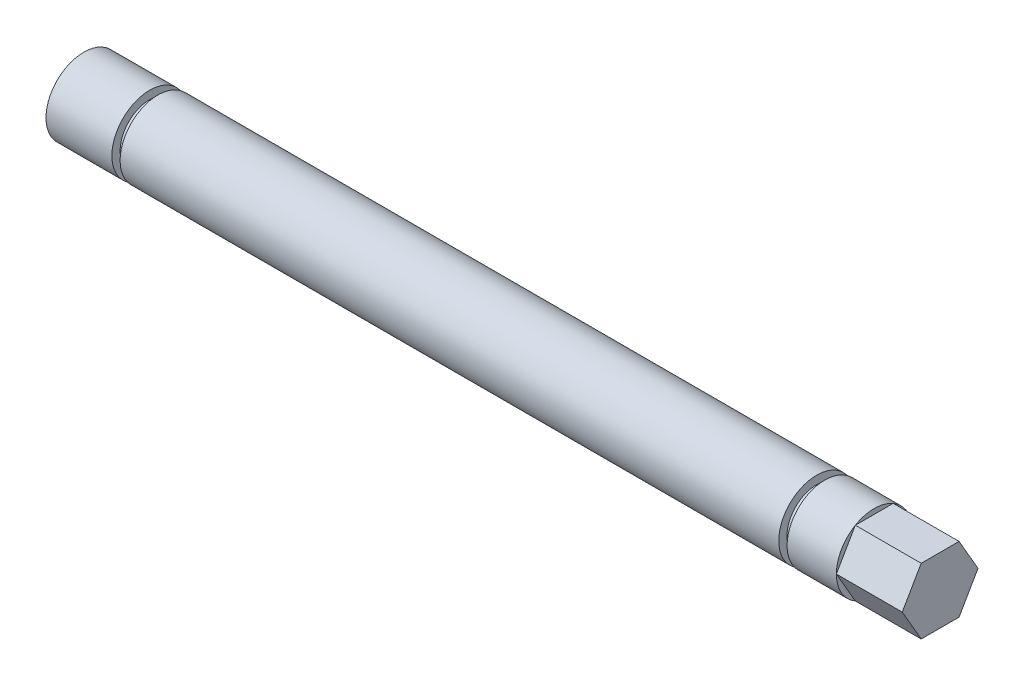
SolidWorks part; units mm, degrees
material "Chrome Stainless Steel"
ref_plane "Front Plane" through (0, 0, 0) normal (0, 0, 1) x (1, 0, 0)
ref_plane "Top Plane" through (0, 0, 0) normal (0, 1, 0) x (1, 0, 0)
ref_plane "Right Plane" through (0, 0, 0) normal (1, 0, 0) x (0, 0, -1)
sketch "Sketch1" plane through (0, 0, 0) normal (1, 0, 0) x (0, 0, -1)
  circle A0 centre (0, 0) radius 7.3025
  dimension "D1" = 14.605
extrude "Boss-Extrude1" add sketch "Sketch1" along normal blind 165.1
sketch "Sketch2" plane through (0, 0, 0) normal (0, 0, 1) x (1, 0, 0)
  line L0 (165.1, 7.3025) -> (0, 7.3025) construction
  line L1 (12.7, 7.3025) -> (14.2875, 7.3025)
  line L2 (12.7, 7.3025) -> (12.7, 5.715)
  line L3 (12.7, 5.715) -> (14.2875, 5.715)
  line L4 (14.2875, 7.3025) -> (14.2875, 5.715)
  line L5 (0, 0) -> (17.729, 0) construction
  line L6 (0, 7.3025) -> (0, -7.3025) construction
  dimension "D1" = 12.7
  dimension "D2" = 1.5875
  dimension "D3" = 1.5875
revolve "Groove" cut sketch "Sketch2" angle 360 about L5
ref_plane "Offset Plane" through (141.2875, 0, 0) normal (-1, 0, 0) x (0, 0, 1)
sketch "Sketch4" plane through (141.2875, 0, 0) normal (-1, 0, 0) x (0, 0, 1)
  circle A0 centre (0, 0) radius 7.3025 construction
  circle A1 centre (0, 0) radius 5.715 construction
  circle A2 centre (0, 0) radius 7.3025
  circle A3 centre (0, 0) radius 5.715
extrude "Cut-Extrude1" cut sketch "Sketch4" against normal blind 1.6002
sketch "Sketch5" plane through (165.1, 0, 0) normal (1, 0, 0) x (0, 0, -1)
  line L1 (7.3025, 0) -> (3.6512, 6.3242)
  line L2 (3.6512, 6.3242) -> (-3.6512, 6.3242)
  line L3 (-3.6512, 6.3242) -> (-7.3025, 0)
  line L4 (-7.3025, 0) -> (-3.6513, -6.3242)
  line L5 (-3.6513, -6.3242) -> (3.6513, -6.3242)
  line L6 (3.6513, -6.3242) -> (7.3025, 0)
  circle A0 centre (0, 0) radius 7.3025 construction
  circle A1 centre (0, 0) radius 7.3025 construction
extrude "Cut-Extrude2" cut sketch "Sketch5" against normal blind 12.7 flip side to cut
